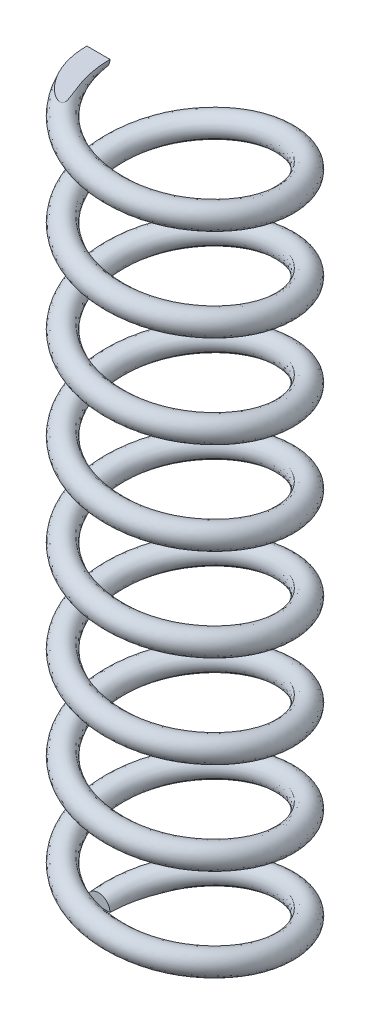
SolidWorks part; units mm, degrees
material "AISI 304"
ref_plane "Front Plane" through (0, 0, 0) normal (0, 0, 1) x (1, 0, 0)
ref_plane "Top Plane" through (0, 0, 0) normal (0, 1, 0) x (1, 0, 0)
ref_plane "Right Plane" through (0, 0, 0) normal (1, 0, 0) x (0, 0, -1)
sketch "Sketch2" plane through (0, 0, 0) normal (0, 1, 0) x (1, 0, 0)
  circle A0 centre (0, 0) radius 0.75
  dimension "D1" = 1.5
curve "Helix/Spiral1" pitch 0.8 height 6.4 turns 8
sketch "Sketch3" plane through (0, 0, 0) normal (0, 0, 1) x (1, 0, 0)
  circle A0 centre (-0.75, 0) radius 0.1
  spline S0 degree 3 poles (-0.75, 0) (-0.75, 0.0166) (-0.7109, 0.05) (-0.5441, 0.1) (-0.2945, 0.15) (0, 0.2) (0.2945, 0.25) (0.5441, 0.3) (0.7109, 0.35) (0.7695, 0.4) (0.7109, 0.45) (0.5441, 0.5) (0.2945, 0.55) (0, 0.6) (-0.2945, 0.65) (-0.5441, 0.7) (-0.7109, 0.75) (-0.7695, 0.8) (-0.7109, 0.85) (-0.5441, 0.9) (-0.2945, 0.95) (0, 1) (0.2945, 1.05) (0.5441, 1.1) (0.7109, 1.15) (0.7695, 1.2) (0.7109, 1.25) (0.5441, 1.3) (0.2945, 1.35) (0, 1.4) (-0.2945, 1.45) (-0.5441, 1.5) (-0.7109, 1.55) (-0.7695, 1.6) (-0.7109, 1.65) (-0.5441, 1.7) (-0.2945, 1.75) (0, 1.8) (0.2945, 1.85) (0.5441, 1.9) (0.7109, 1.95) (0.7695, 2) (0.7109, 2.05) (0.5441, 2.1) (0.2945, 2.15) (0, 2.2) (-0.2945, 2.25) (-0.5441, 2.3) (-0.7109, 2.35) (-0.7695, 2.4) (-0.7109, 2.45) (-0.5441, 2.5) (-0.2945, 2.55) (0, 2.6) (0.2945, 2.65) (0.5441, 2.7) (0.7109, 2.75) (0.7695, 2.8) (0.7109, 2.85) (0.5441, 2.9) (0.2945, 2.95) (0, 3) (-0.2945, 3.05) (-0.5441, 3.1) (-0.7109, 3.15) (-0.7695, 3.2) (-0.7109, 3.25) (-0.5441, 3.3) (-0.2945, 3.35) (0, 3.4) (0.2945, 3.45) (0.5441, 3.5) (0.7109, 3.55) (0.7695, 3.6) (0.7109, 3.65) (0.5441, 3.7) (0.2945, 3.75) (0, 3.8) (-0.2945, 3.85) (-0.5441, 3.9) (-0.7109, 3.95) (-0.7695, 4) (-0.7109, 4.05) (-0.5441, 4.1) (-0.2945, 4.15) (0, 4.2) (0.2945, 4.25) (0.5441, 4.3) (0.7109, 4.35) (0.7695, 4.4) (0.7109, 4.45) (0.5441, 4.5) (0.2945, 4.55) (0, 4.6) (-0.2945, 4.65) (-0.5441, 4.7) (-0.7109, 4.75) (-0.7695, 4.8) (-0.7109, 4.85) (-0.5441, 4.9) (-0.2945, 4.95) (0, 5) (0.2945, 5.05) (0.5441, 5.1) (0.7109, 5.15) (0.7695, 5.2) (0.7109, 5.25) (0.5441, 5.3) (0.2945, 5.35) (0, 5.4) (-0.2945, 5.45) (-0.5441, 5.5) (-0.7109, 5.55) (-0.7695, 5.6) (-0.7109, 5.65) (-0.5441, 5.7) (-0.2945, 5.75) (0, 5.8) (0.2945, 5.85) (0.5441, 5.9) (0.7109, 5.95) (0.7695, 6) (0.7109, 6.05) (0.5441, 6.1) (0.2945, 6.15) (0, 6.2) (-0.2945, 6.25) (-0.5441, 6.3) (-0.7109, 6.35) (-0.75, 6.3834) (-0.75, 6.4) knots 0 0 0 0 0.007813 0.015625 0.023438 0.03125 0.039063 0.046875 0.054688 0.0625 0.070313 0.078125 0.085938 0.09375 0.101563 0.109375 0.117188 0.125 0.132813 0.140625 0.148438 0.15625 0.164063 0.171875 0.179688 0.1875 0.195313 0.203125 0.210938 0.21875 0.226563 0.234375 0.242188 0.25 0.257813 0.265625 0.273438 0.28125 0.289063 0.296875 0.304688 0.3125 0.320313 0.328125 0.335938 0.34375 0.351563 0.359375 0.367188 0.375 0.382813 0.390625 0.398438 0.40625 0.414063 0.421875 0.429688 0.4375 0.445313 0.453125 0.460938 0.46875 0.476563 0.484375 0.492188 0.5 0.507813 0.515625 0.523438 0.53125 0.539062 0.546875 0.554687 0.5625 0.570312 0.578125 0.585937 0.59375 0.601562 0.609375 0.617187 0.625 0.632812 0.640625 0.648437 0.65625 0.664062 0.671875 0.679687 0.6875 0.695312 0.703125 0.710937 0.71875 0.726562 0.734375 0.742187 0.75 0.757812 0.765625 0.773437 0.78125 0.789062 0.796875 0.804687 0.8125 0.820312 0.828125 0.835937 0.84375 0.851562 0.859375 0.867187 0.875 0.882812 0.890625 0.898437 0.90625 0.914062 0.921875 0.929687 0.9375 0.945312 0.953125 0.960937 0.96875 0.976562 0.984375 0.992188 1 1 1 1 construction
  dimension "D1" = 0.2
sweep "Sweep2" add profiles "Sketch3" path "Helix/Spiral1"
sketch "Sketch4" plane through (0, 0, 0) normal (1, 0, 0) x (0, 0, -1)
  line L1 (-2, 7.1063) -> (2, 7.1063)
  line L2 (-2, 7.1063) -> (-2, 6.4)
  line L3 (-2, 6.4) -> (2, 6.4)
  line L4 (2, 7.1063) -> (2, 6.4)
  line L5 (-2, 0) -> (2, 0)
  line L6 (-2, 0) -> (-2, -0.5)
  line L7 (-2, -0.5) -> (2, -0.5)
  line L8 (2, 0) -> (2, -0.5)
  dimension "D1" = 6.4
  dimension "D2" = 4
  dimension "D3" = 0.5
extrude "Cut-Extrude1" cut sketch "Sketch4" against normal mid plane 10
